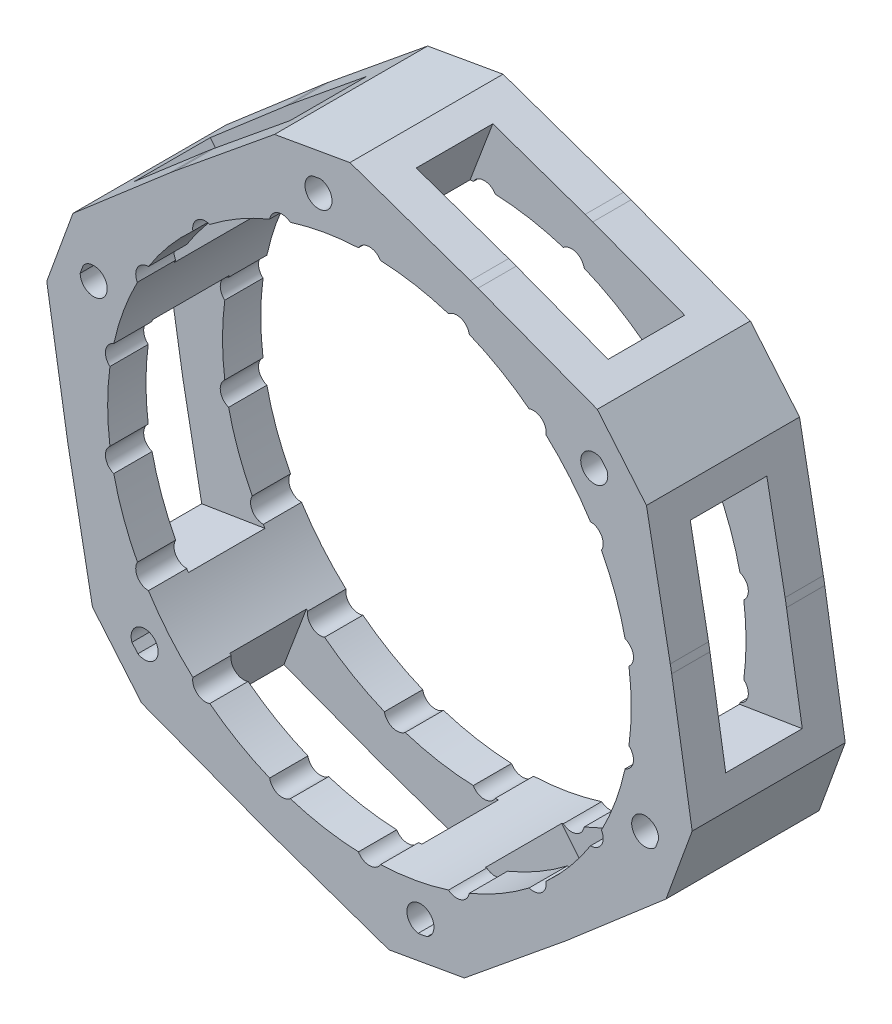
SolidWorks part; units mm, degrees
ref_plane "Front Plane" through (0, 0, 0) normal (0, 0, 1) x (1, 0, 0)
ref_plane "Top Plane" through (0, 0, 0) normal (0, 1, 0) x (1, 0, 0)
ref_plane "Right Plane" through (0, 0, 0) normal (1, 0, 0) x (0, 0, -1)
sketch "Sketch1" plane through (0, 0, 0) normal (0, 0, 1) x (1, 0, 0)
  line L0 (0, 50) -> (0, 0) construction
  circle A2 centre (0, 0) radius 60
  arc A60 (15.4979, 48.903) -> (2.1625, 51.2544) centre (0, 0) ccw
  arc A64 (2.1625, 51.2544) -> (-2.1625, 51.2544) centre (0, 50) ccw
  arc A66 (19.5621, 47.4238) -> (15.4979, 48.903) centre (17.101, 46.9846) ccw
  arc A68 (34.6023, 37.8731) -> (31.2891, 40.6532) centre (32.1394, 38.3022) ccw
  arc A70 (45.4689, 23.7544) -> (43.3064, 27.5) centre (43.3013, 25) ccw
  arc A72 (50.8512, 6.7706) -> (50.1002, 11.0299) centre (49.2404, 8.6824) ccw
  arc A74 (50.1002, -11.0299) -> (50.8512, -6.7706) centre (49.2404, -8.6824) ccw
  arc A76 (43.3064, -27.5) -> (45.4689, -23.7544) centre (43.3013, -25) ccw
  arc A78 (31.2891, -40.6532) -> (34.6023, -37.8731) centre (32.1394, -38.3022) ccw
  arc A80 (15.4979, -48.903) -> (19.5621, -47.4238) centre (17.101, -46.9846) ccw
  arc A82 (-2.1625, -51.2544) -> (2.1625, -51.2544) centre (0, -50) ccw
  arc A84 (-19.5621, -47.4238) -> (-15.4979, -48.903) centre (-17.101, -46.9846) ccw
  arc A86 (-34.6023, -37.8731) -> (-31.2891, -40.6532) centre (-32.1394, -38.3022) ccw
  arc A88 (-45.4689, -23.7544) -> (-43.3064, -27.5) centre (-43.3013, -25) ccw
  arc A90 (-50.8512, -6.7706) -> (-50.1002, -11.0299) centre (-49.2404, -8.6824) ccw
  arc A92 (-50.1002, 11.0299) -> (-50.8512, 6.7706) centre (-49.2404, 8.6824) ccw
  arc A94 (-43.3064, 27.5) -> (-45.4689, 23.7544) centre (-43.3013, 25) ccw
  arc A110 (31.2891, 40.6532) -> (19.5621, 47.4238) centre (0, 0) ccw
  arc A111 (43.3064, 27.5) -> (34.6023, 37.8731) centre (0, 0) ccw
  arc A112 (50.1002, 11.0299) -> (45.4689, 23.7544) centre (0, 0) ccw
  arc A113 (50.8512, -6.7706) -> (50.8512, 6.7706) centre (0, 0) ccw
  arc A114 (45.4689, -23.7544) -> (50.1002, -11.0299) centre (0, 0) ccw
  arc A115 (34.6023, -37.8731) -> (43.3064, -27.5) centre (0, 0) ccw
  arc A116 (19.5621, -47.4238) -> (31.2891, -40.6532) centre (0, 0) ccw
  arc A117 (2.1625, -51.2544) -> (15.4979, -48.903) centre (0, 0) ccw
  arc A118 (-15.4979, -48.903) -> (-2.1625, -51.2544) centre (0, 0) ccw
  arc A119 (-31.2891, -40.6532) -> (-19.5621, -47.4238) centre (0, 0) ccw
  arc A120 (-43.3064, -27.5) -> (-34.6023, -37.8731) centre (0, 0) ccw
  arc A121 (-50.1002, -11.0299) -> (-45.4689, -23.7544) centre (0, 0) ccw
  arc A122 (-50.8512, 6.7706) -> (-50.8512, -6.7706) centre (0, 0) ccw
  arc A123 (-45.4689, 23.7544) -> (-50.1002, 11.0299) centre (0, 0) ccw
  arc A124 (-34.6023, 37.8731) -> (-43.3064, 27.5) centre (0, 0) ccw
  arc A125 (-19.5621, 47.4238) -> (-31.2891, 40.6532) centre (0, 0) ccw
  arc A127 (-31.2891, 40.6532) -> (-34.6023, 37.8731) centre (-32.1394, 38.3022) ccw
  arc A128 (-15.4979, 48.903) -> (-19.5621, 47.4238) centre (-17.101, 46.9846) ccw
  arc A129 (-2.1625, 51.2544) -> (-15.4979, 48.903) centre (0, 0) ccw
  point P38 (0, 0)
  point P40 (0, 0)
  point P59 (0, 0)
  point P85 (0, 0)
  dimension "D1" = 50
  dimension "D3" = 120
  dimension "D6" = 18
  dimension "D5" = 5
  dimension "D7" = 102.6
extrude "Boss-Extrude1" add sketch "Sketch1" along normal blind 30
sketch "Sketch2" plane through (0, 0, 30) normal (0, 0, 1) x (1, 0, 0)
  line L0 (0, 0) -> (0, 60) construction
  line L1 (0, 0) -> (-9.9848, 56.6264) construction
  circle A0 centre (0, 0) radius 57.5 construction
  circle A1 centre (-9.9848, 56.6264) radius 2.65
  circle A2 centre (0, 0) radius 60 construction
  circle A3 centre (44.0476, 36.9603) radius 2.65
  circle A4 centre (54.0323, -19.6662) radius 2.65
  circle A5 centre (9.9848, -56.6264) radius 2.65
  circle A6 centre (-44.0476, -36.9603) radius 2.65
  circle A7 centre (-54.0323, 19.6662) radius 2.65
  point P22 (0, 0)
  dimension "D1" = 115
  dimension "D2" = 5.3
  dimension "D3" = 10
  dimension "D4" = 6
extrude "Cut-Extrude2" cut sketch "Sketch2" against normal through all
sketch "Sketch3" plane through (0, 0, 30) normal (0, 0, 1) x (1, 0, 0)
  line L0 (0, 0) -> (-9.9848, 56.6264) construction
  line L1 (-9.9848, 56.6264) -> (-11.2871, 64.0125) construction
  line L2 (0, 65) -> (0, 0) construction
  line L3 (-37.9588, 46.4664) -> (-18.5978, 62.2826)
  line L4 (-18.5978, 62.2826) -> (-3.8257, 64.8873)
  line L5 (-3.8257, 64.8873) -> (19.7772, 56.6468)
  line L6 (54.2812, 35.7568) -> (58.9462, 11.1959)
  line L7 (44.6394, 47.2475) -> (54.2812, 35.7568)
  line L8 (21.2617, 56.1065) -> (44.6394, 47.2475)
  line L9 (58.1069, -29.1305) -> (39.169, -45.4509)
  line L10 (63.2372, -15.0351) -> (58.1069, -29.1305)
  line L11 (59.2205, 9.6401) -> (63.2372, -15.0351)
  line L12 (3.8257, -64.8873) -> (-19.7772, -56.6468)
  line L13 (18.5978, -62.2826) -> (3.8257, -64.8873)
  line L14 (37.9588, -46.4664) -> (18.5978, -62.2826)
  line L15 (-54.2812, -35.7568) -> (-58.9462, -11.1959)
  line L16 (-44.6394, -47.2475) -> (-54.2812, -35.7568)
  line L17 (-21.2617, -56.1065) -> (-44.6394, -47.2475)
  line L18 (-58.1069, 29.1305) -> (-39.169, 45.4509)
  line L19 (-63.2372, 15.0351) -> (-58.1069, 29.1305)
  line L20 (-59.2205, -9.6401) -> (-63.2372, 15.0351)
  circle A0 centre (0, 0) radius 65 construction
  circle A1 centre (0, 0) radius 60 construction
  arc A2 (-37.9588, 46.4664) -> (19.7772, 56.6468) centre (0, 0) cw
  arc A3 (21.2617, 56.1065) -> (58.9462, 11.1959) centre (0, 0) cw
  arc A4 (59.2205, 9.6401) -> (39.169, -45.4509) centre (0, 0) cw
  arc A5 (37.9588, -46.4664) -> (-19.7772, -56.6468) centre (0, 0) cw
  arc A6 (-21.2617, -56.1065) -> (-58.9462, -11.1959) centre (0, 0) cw
  arc A7 (-59.2205, -9.6401) -> (-39.169, 45.4509) centre (0, 0) cw
  point P11 (-11.2117, 63.585)
  point P38 (0, 0)
  dimension "D1" = 130
  dimension "D2" = 15
  dimension "D3" = 6
extrude "Boss-Extrude2" add sketch "Sketch3" against normal blind 30
sketch "Sketch4" plane through (-59.2205, -9.6401, 0) normal (-0.987, -0.1607, 0) x (0, 0, 1)
  line L0 (15, 25) -> (15, -26.5) construction
  line L1 (0, 25) -> (30, 25) construction
  line L2 (0, 25) -> (0, -26.5) construction
  line L3 (0, -26.5) -> (30, -26.5) construction
  line L4 (30, 25) -> (30, -26.5) construction
  line L6 (7.5, 19.25) -> (22.5, 19.25)
  line L7 (7.5, 19.25) -> (7.5, -20.75)
  line L8 (7.5, -20.75) -> (22.5, -20.75)
  line L9 (22.5, 19.25) -> (22.5, -20.75)
  line L10 (7.5, 19.25) -> (22.5, -20.75) construction
  line L11 (7.5, -20.75) -> (22.5, 19.25) construction
  point P7 (15, -0.75)
  dimension "D1" = 30
  dimension "D2" = 51.5
  dimension "D3" = 40
  dimension "D4" = 15
extrude "Cut-Extrude3" cut sketch "Sketch4" against normal blind 22
pattern_circular "CirPattern1" count 6 over 360 about axis through (0, 0, 0) along (0, 0, 1) of "Cut-Extrude3"
